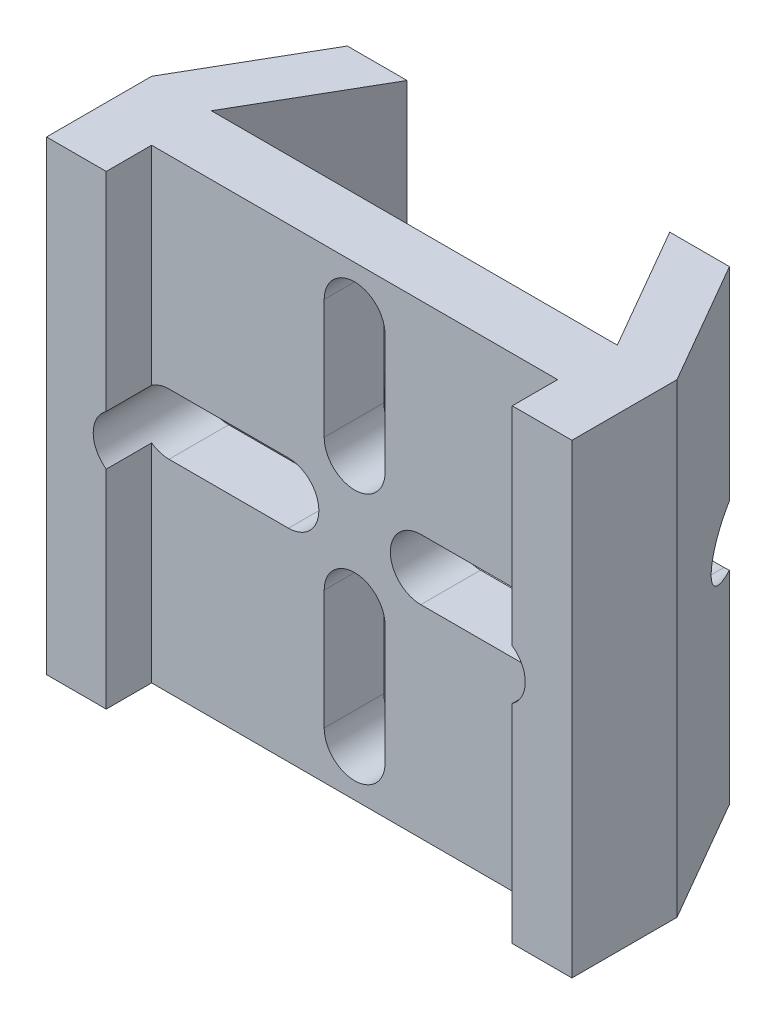
SolidWorks part; units mm, degrees
ref_plane "Front Plane" through (0, 0, 0) normal (0, 0, 1) x (1, 0, 0)
ref_plane "Top Plane" through (0, 0, 0) normal (0, 1, 0) x (1, 0, 0)
ref_plane "Right Plane" through (0, 0, 0) normal (1, 0, 0) x (0, 0, -1)
other "Configuration Table"
sketch "草图1" plane through (0, 0, 0) normal (0, 1, 0) x (1, 0, 0)
  line L0 (-22, 0) -> (22, 0) construction
  line L1 (-22, 0) -> (-22, -3.8)
  line L2 (22, 0) -> (22, -3.8)
  line L3 (-17, 0) -> (17, 0)
  line L4 (-17, 0) -> (-17, -3.8)
  line L5 (-17, -3.8) -> (-22, -3.8)
  line L6 (17, 0) -> (17, -3.8)
  line L7 (17, -3.8) -> (22, -3.8)
  line L8 (-17, 0) -> (-17, 5) construction
  line L9 (-17, 5) -> (17, 5)
  line L10 (17, 5) -> (17, 0) construction
  line L11 (-22, 0) -> (-22, 5)
  line L12 (-22, 5) -> (-16, 15.3923)
  line L13 (-17, 5) -> (-11, 15.3923)
  line L14 (-16, 15.3923) -> (-11, 15.3923)
  line L15 (17, 5) -> (11, 15.3923)
  line L16 (22, 0) -> (22, 5)
  line L17 (22, 5) -> (16, 15.3923)
  line L18 (11, 15.3923) -> (16, 15.3923)
  point P4 (0, 0)
  point P10 (0, 0)
  dimension "D1" = 44
  dimension "D2" = 3.8
  dimension "D3" = 34
  dimension "D4" = 60
  dimension "D5" = 60
  dimension "D6" = 60
extrude "凸台-拉伸1" add sketch "草图1" along normal blind 39
sketch "草图2" plane through (0, 0, 3.8) normal (0, 0, 1) x (1, 0, 0)
  line L0 (0, 0) -> (0, 39) construction
  line L1 (-17, 39) -> (17, 39) construction
  line L2 (-3, 19.5) -> (3, 19.5)
  line L3 (0, 16.5) -> (0, 22.5)
  line L4 (0, 25.0432) -> (0, 35.0432) construction
  line L5 (-2.5485, 25.0432) -> (-2.5485, 35.0432)
  line L6 (2.5485, 25.0432) -> (2.5485, 35.0432)
  line L7 (5.5432, 16.9515) -> (15.5432, 16.9515)
  line L8 (5.5432, 22.0485) -> (15.5432, 22.0485)
  line L9 (5.5432, 19.5) -> (15.5432, 19.5) construction
  line L10 (-2.5485, 13.9568) -> (-2.5485, 3.9568)
  line L11 (2.5485, 13.9568) -> (2.5485, 3.9568)
  line L12 (0, 13.9568) -> (0, 3.9568) construction
  line L13 (-5.5432, 22.0485) -> (-15.5432, 22.0485)
  line L14 (-5.5432, 16.9515) -> (-15.5432, 16.9515)
  line L15 (-5.5432, 19.5) -> (-15.5432, 19.5) construction
  arc A0 (-2.5485, 25.0432) -> (2.5485, 25.0432) centre (0, 25.0432) ccw
  arc A1 (2.5485, 35.0432) -> (-2.5485, 35.0432) centre (0, 35.0432) ccw
  arc A2 (5.5432, 22.0485) -> (5.5432, 16.9515) centre (5.5432, 19.5) ccw
  arc A3 (15.5432, 16.9515) -> (15.5432, 22.0485) centre (15.5432, 19.5) ccw
  arc A4 (2.5485, 13.9568) -> (-2.5485, 13.9568) centre (0, 13.9568) ccw
  arc A5 (-2.5485, 3.9568) -> (2.5485, 3.9568) centre (0, 3.9568) ccw
  arc A6 (-5.5432, 16.9515) -> (-5.5432, 22.0485) centre (-5.5432, 19.5) ccw
  arc A7 (-15.5432, 22.0485) -> (-15.5432, 16.9515) centre (-15.5432, 19.5) ccw
  point P8 (0, 19.5)
  point P11 (0, 19.5)
  point P13 (0, 30.0432)
  point P23 (10.5432, 19.5)
  point P30 (0, 8.9568)
  point P37 (-10.5432, 19.5)
  point P42 (0, 19.5)
  dimension "D1" = 4
extrude "切除-拉伸1" cut sketch "草图2" against normal through all
